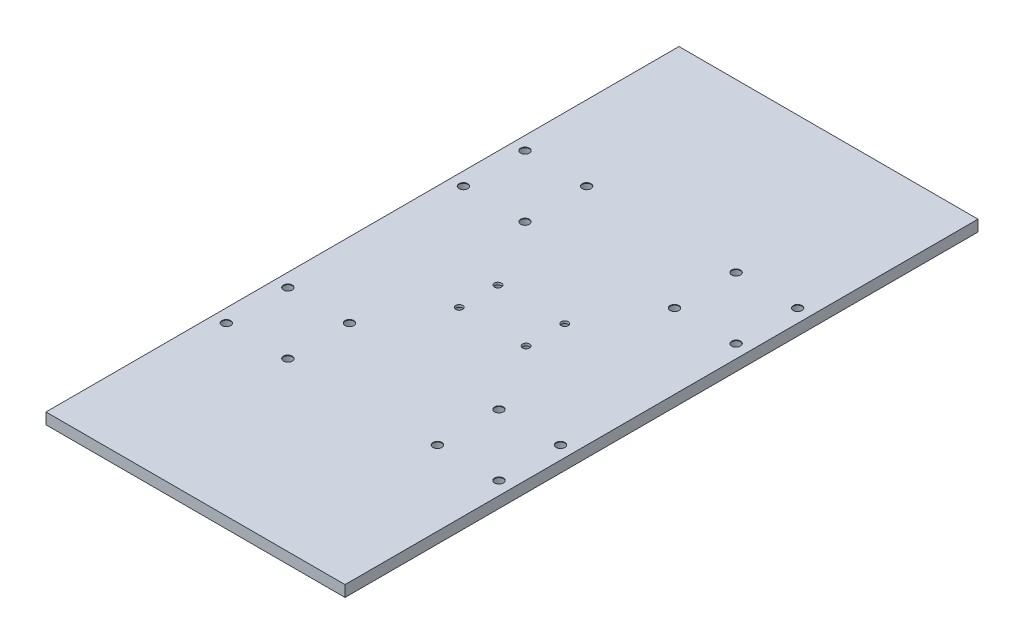
SolidWorks part; units mm, degrees
ref_plane "Front Plane" through (0, 0, 0) normal (0, 0, 1) x (1, 0, 0)
ref_plane "Top Plane" through (0, 0, 0) normal (0, 1, 0) x (1, 0, 0)
ref_plane "Right Plane" through (0, 0, 0) normal (1, 0, 0) x (0, 0, -1)
ref_plane "Plane1"
sketch "Sketch1" plane through (0, 0, 0) normal (0, 1, 0) x (-1, 0, 0)
  line L0 (85, 179.925) -> (-85, 179.925)
  line L1 (-85, 179.925) -> (-85, -179.925)
  line L2 (-85, -179.925) -> (85, -179.925)
  line L3 (85, -179.925) -> (85, 179.925)
extrude "Extrusion1" add sketch "Sketch1" along normal blind 6.35
hole_wizard "Hole2" positions "Sketch3" profile "Sketch2" legacy
sketch "Sketch3" plane through (0, 0, 0) normal (0, -1, 0) x (-1, 0, 0)
  point P1 (19, -11)
  point P2 (-19, -11)
  point P3 (-19, 11)
  point P4 (19, 11)
sketch "Sketch2" plane through (-19, 0, 11) normal (1, 0, 0) x (0, 0, -1)
  line L0 (0, 0) -> (0, 9.2017)
  line L1 (0, 9.2017) -> (2, 8)
  line L2 (2, 8) -> (2, 0)
  line L4 (2, 0) -> (0, 0)
  line L6 (0, 9.2017) -> (-2, 8) construction
  line L7 (0, -4.2442) -> (0, 117.3081) construction
  dimension "Diameter" = 4
  dimension "Depth" = 8
  dimension "Drill Angle" = 118
hole_wizard "Hole3" positions "Sketch5" profile "Sketch4" legacy
sketch "Sketch5" plane through (0, 0, 0) normal (0, -1, 0) x (-1, 0, 0)
  point P1 (-42.5, -84.9)
  point P2 (-77.5, -84.9)
  point P3 (-42.5, -49.9)
  point P4 (-77.5, -49.9)
  point P5 (42.5, -49.9)
  point P6 (77.5, -49.9)
  point P7 (42.5, -84.9)
  point P8 (77.5, -84.9)
  point P9 (-77.5, 84.9)
  point P10 (-42.5, 84.9)
  point P11 (-77.5, 49.9)
  point P12 (-42.5, 49.9)
  point P13 (42.5, 84.9)
  point P14 (77.5, 84.9)
  point P15 (42.5, 49.9)
  point P16 (77.5, 49.9)
sketch "Sketch4" plane through (42.5, 0, 84.9) normal (1, 0, 0) x (0, 0, -1)
  line L0 (0, 0) -> (0, 9.5022)
  line L1 (0, 9.5022) -> (2.5, 8)
  line L2 (2.5, 8) -> (2.5, 0)
  line L4 (2.5, 0) -> (0, 0)
  line L6 (0, 9.5022) -> (-2.5, 8) construction
  line L7 (0, -4.2442) -> (0, 117.3081) construction
  dimension "Diameter" = 5
  dimension "Depth" = 8
  dimension "Drill Angle" = 118
ref_plane "Plane2" through (-19, 0, 11) normal (0, -1, 0) x (0, 0, -1)
hole_wizard "Hole4" positions "Sketch7" profile "Sketch6" legacy
sketch "Sketch7" plane through (-19, 0, 11) normal (0, -1, 0) x (0, 0, -1)
  point P1 (0, 0)
  point P2 (0, 38)
  point P3 (22, 38)
  point P4 (22, 0)
sketch "Sketch6" plane through (-19, 0, 11) normal (1, 0, 0) x (0, 0, -1)
  line L0 (0, 0) -> (0, 5)
  line L1 (0, 5) -> (4.875, 5)
  line L2 (4.875, 5) -> (4.875, 0)
  line L3 (4.875, 0) -> (0, 0)
  line L4 (0, 110) -> (0, -10) construction
  dimension "Diameter" = 9.75
  dimension "Depth" = 5
ref_plane "Plane3" through (-77.5, 0, 49.9) normal (0, -1, 0) x (0, 0, -1)
hole_wizard "Hole5" positions "Sketch9" profile "Sketch8" legacy
sketch "Sketch9" plane through (-77.5, 0, 49.9) normal (0, -1, 0) x (0, 0, -1)
  point P1 (0, 0)
  point P2 (0, 35)
  point P3 (-35, 35)
  point P4 (-35, 0)
  point P5 (-35, 120)
  point P6 (-35, 155)
  point P7 (0, 155)
  point P8 (0, 120)
  point P9 (99.8, 155)
  point P10 (99.8, 120)
  point P11 (134.8, 120)
  point P12 (134.8, 155)
  point P13 (134.8, 35)
  point P14 (99.8, 35)
  point P15 (99.8, 0)
  point P16 (134.8, 0)
sketch "Sketch8" plane through (-77.5, 0, 49.9) normal (1, 0, 0) x (0, 0, -1)
  line L0 (0, 0) -> (0, 6)
  line L1 (0, 6) -> (5.6, 6)
  line L2 (5.6, 6) -> (5.6, 0)
  line L3 (5.6, 0) -> (0, 0)
  line L4 (0, 110) -> (0, -10) construction
  dimension "Diameter" = 11.2
  dimension "Depth" = 6
